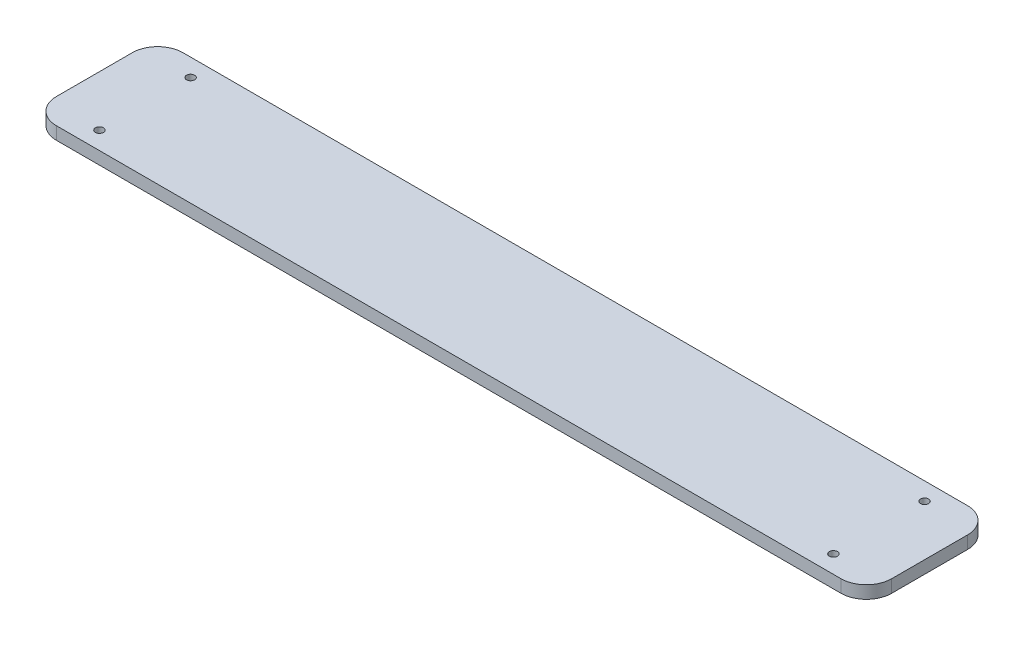
SolidWorks part; units mm, degrees
ref_plane "Front Plane" through (0, 0, 0) normal (0, 0, 1) x (1, 0, 0)
ref_plane "Top Plane" through (0, 0, 0) normal (0, 1, 0) x (1, 0, 0)
ref_plane "Right Plane" through (0, 0, 0) normal (1, 0, 0) x (0, 0, -1)
sketch "Sketch1" plane through (0, 0, 0) normal (0, 1, 0) x (1, 0, 0)
  line L0 (20, 50) -> (20, 0) construction
  line L1 (0, 0) -> (330, 0)
  line L2 (0, 0) -> (0, 50)
  line L3 (0, 50) -> (330, 50)
  line L4 (330, 0) -> (330, 50)
  line L5 (0, 25) -> (165, 25) construction
  line L6 (165, 50) -> (165, 0) construction
  circle A0 centre (20, 43) radius 1.6
  circle A1 centre (20, 7) radius 1.6
  circle A2 centre (310, 7) radius 1.6
  circle A3 centre (310, 43) radius 1.6
  dimension "D4" = 3.2
  dimension "D5" = 36
  dimension "D1" = 330
  dimension "D2" = 50
  dimension "D3" = 20
  dimension "D6" = 18
extrude "Boss-Extrude1" add sketch "Sketch1" along normal blind 5
fillet "Fillet1" radius 10 4 edges at (330, 2.5, 0) (330, 2.5, -50) (0, 2.5, 0) (0, 2.5, -50)
